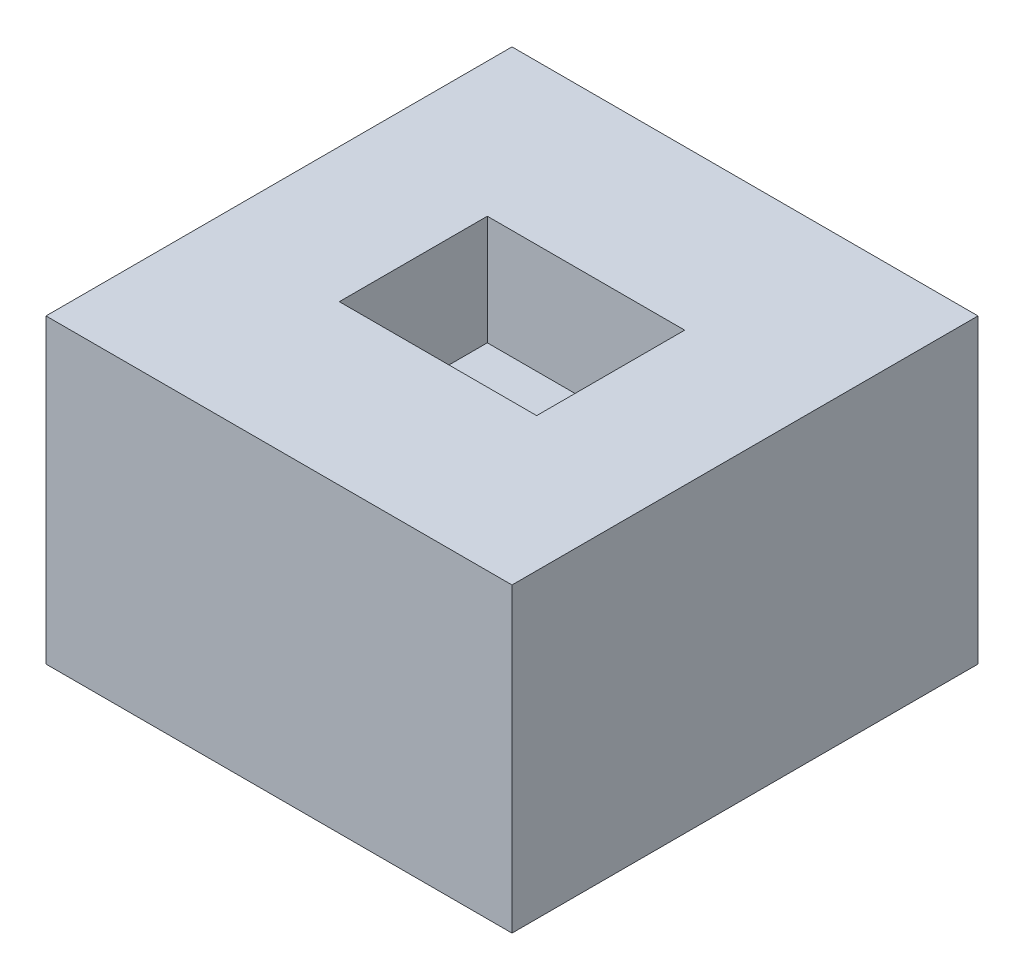
SolidWorks part; units mm, degrees
material "Nickel"
ref_plane "Front Plane" through (0, 0, 0) normal (0, 0, 1) x (1, 0, 0)
ref_plane "Top Plane" through (0, 0, 0) normal (0, 1, 0) x (1, 0, 0)
ref_plane "Right Plane" through (0, 0, 0) normal (1, 0, 0) x (0, 0, -1)
sketch "Sketch1" plane through (0, 0, 0) normal (0, 1, 0) x (1, 0, 0)
  line L1 (4.25, -4.25) -> (-4.25, -4.25)
  line L2 (4.25, -4.25) -> (4.25, 4.25)
  line L3 (4.25, 4.25) -> (-4.25, 4.25)
  line L4 (-4.25, -4.25) -> (-4.25, 4.25)
  line L5 (4.25, -4.25) -> (-4.25, 4.25) construction
  line L6 (4.25, 4.25) -> (-4.25, -4.25) construction
  point P0 (0, 0)
  dimension "D1" = 8.5
extrude "Boss-Extrude1" add sketch "Sketch1" along normal blind 5.5
sketch "Sketch2" plane through (0, 5.5, 0) normal (0, 1, 0) x (1, 0, 0)
  line L1 (-1.8, -1.35) -> (1.8, -1.35)
  line L2 (-1.8, -1.35) -> (-1.8, 1.35)
  line L3 (-1.8, 1.35) -> (1.8, 1.35)
  line L4 (1.8, -1.35) -> (1.8, 1.35)
  line L5 (-1.8, -1.35) -> (1.8, 1.35) construction
  line L6 (-1.8, 1.35) -> (1.8, -1.35) construction
  point P0 (0, 0)
  dimension "D1" = 3.6
  dimension "D2" = 2.7
extrude "Cut-Extrude1" cut sketch "Sketch2" against normal blind 2
